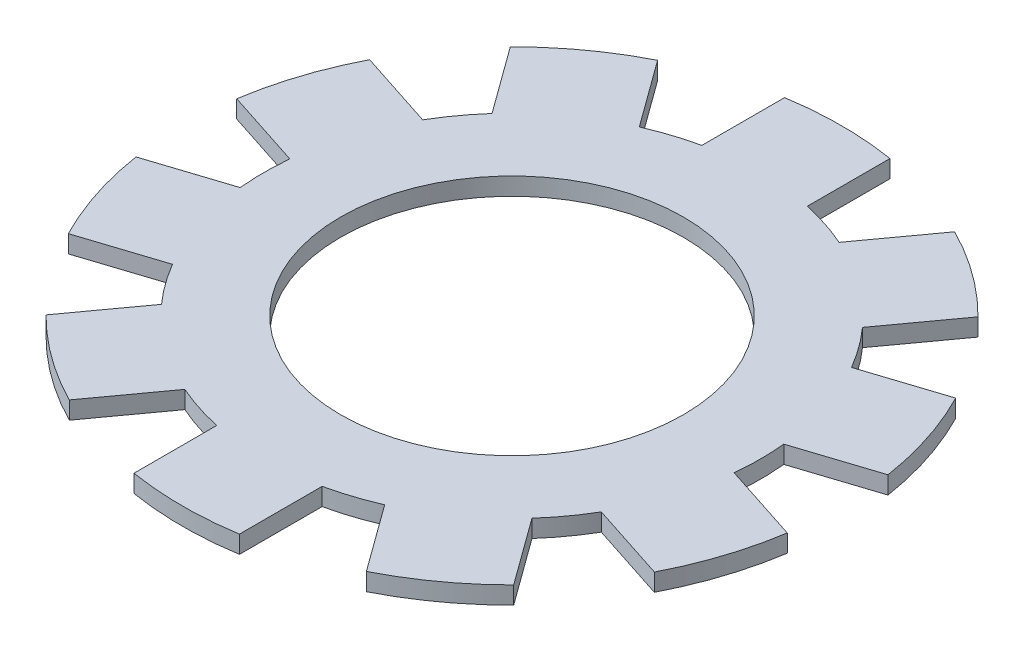
SolidWorks part; units mm, degrees
material "6061 Alloy"
ref_plane "Front Plane" through (0, 0, 0) normal (0, 0, 1) x (1, 0, 0)
ref_plane "Top Plane" through (0, 0, 0) normal (0, 1, 0) x (1, 0, 0)
ref_plane "Right Plane" through (0, 0, 0) normal (1, 0, 0) x (0, 0, -1)
sketch "Sketch1" plane through (0, 0, 0) normal (0, 1, 0) x (1, 0, 0)
  line L0 (-1.2, 5.5211) -> (-1.2, 7.4034)
  line L1 (1.2, 7.4034) -> (1.2, 5.5211)
  line L2 (0, 0) -> (0, 50000) construction
  line L3 (2.2744, 5.172) -> (3.3808, 6.6948)
  line L4 (5.3224, 5.2841) -> (4.216, 3.7613)
  line L5 (4.8801, 2.8474) -> (6.6702, 3.429)
  line L6 (7.4119, 1.1465) -> (5.6217, 0.5648)
  line L7 (5.6217, -0.5648) -> (7.4119, -1.1465)
  line L8 (6.6702, -3.429) -> (4.8801, -2.8474)
  line L9 (4.216, -3.7613) -> (5.3224, -5.2841)
  line L10 (3.3808, -6.6948) -> (2.2744, -5.172)
  line L11 (1.2, -5.5211) -> (1.2, -7.4034)
  line L12 (-1.2, -7.4034) -> (-1.2, -5.5211)
  line L13 (-2.2744, -5.172) -> (-3.3808, -6.6948)
  line L14 (-5.3224, -5.2841) -> (-4.216, -3.7613)
  line L15 (-4.8801, -2.8474) -> (-6.6702, -3.429)
  line L16 (-7.4119, -1.1465) -> (-5.6217, -0.5648)
  line L17 (-5.6217, 0.5648) -> (-7.4119, 1.1465)
  line L18 (-6.6702, 3.429) -> (-4.8801, 2.8474)
  line L19 (-4.216, 3.7613) -> (-5.3224, 5.2841)
  line L20 (-3.3808, 6.6948) -> (-2.2744, 5.172)
  circle A0 centre (0, 0) radius 7.5 construction
  circle A1 centre (0, 0) radius 3.9
  circle A2 centre (0, 0) radius 5.65 construction
  arc A3 (0, 7.5) -> (-1.2, 7.4034) centre (0, 0) ccw
  arc A4 (0, 7.5) -> (1.2, 7.4034) centre (0, 0) cw
  arc A5 (4.4084, 6.0676) -> (5.3224, 5.2841) centre (0, 0) cw
  arc A6 (4.4084, 6.0676) -> (3.3808, 6.6948) centre (0, 0) ccw
  arc A7 (7.1329, 2.3176) -> (7.4119, 1.1465) centre (0, 0) cw
  arc A8 (7.1329, 2.3176) -> (6.6702, 3.429) centre (0, 0) ccw
  arc A9 (7.1329, -2.3176) -> (6.6702, -3.429) centre (0, 0) cw
  arc A10 (7.1329, -2.3176) -> (7.4119, -1.1465) centre (0, 0) ccw
  arc A11 (4.4084, -6.0676) -> (3.3808, -6.6948) centre (0, 0) cw
  arc A12 (4.4084, -6.0676) -> (5.3224, -5.2841) centre (0, 0) ccw
  arc A13 (0, -7.5) -> (-1.2, -7.4034) centre (0, 0) cw
  arc A14 (0, -7.5) -> (1.2, -7.4034) centre (0, 0) ccw
  arc A15 (-4.4084, -6.0676) -> (-5.3224, -5.2841) centre (0, 0) cw
  arc A16 (-4.4084, -6.0676) -> (-3.3808, -6.6948) centre (0, 0) ccw
  arc A17 (-7.1329, -2.3176) -> (-7.4119, -1.1465) centre (0, 0) cw
  arc A18 (-7.1329, -2.3176) -> (-6.6702, -3.429) centre (0, 0) ccw
  arc A19 (-7.1329, 2.3176) -> (-6.6702, 3.429) centre (0, 0) cw
  arc A20 (-7.1329, 2.3176) -> (-7.4119, 1.1465) centre (0, 0) ccw
  arc A21 (-4.4084, 6.0676) -> (-3.3808, 6.6948) centre (0, 0) cw
  arc A22 (-4.4084, 6.0676) -> (-5.3224, 5.2841) centre (0, 0) ccw
  arc A23 (-1.2, 5.5211) -> (-2.2744, 5.172) centre (0, 0) ccw
  arc A24 (2.2744, 5.172) -> (1.2, 5.5211) centre (0, 0) ccw
  arc A25 (4.8801, 2.8474) -> (4.216, 3.7613) centre (0, 0) ccw
  arc A26 (5.6217, -0.5648) -> (5.6217, 0.5648) centre (0, 0) ccw
  arc A27 (4.216, -3.7613) -> (4.8801, -2.8474) centre (0, 0) ccw
  arc A28 (1.2, -5.5211) -> (2.2744, -5.172) centre (0, 0) ccw
  arc A29 (-2.2744, -5.172) -> (-1.2, -5.5211) centre (0, 0) ccw
  arc A30 (-4.8801, -2.8474) -> (-4.216, -3.7613) centre (0, 0) ccw
  arc A31 (-5.6217, 0.5648) -> (-5.6217, -0.5648) centre (0, 0) ccw
  arc A32 (-4.216, 3.7613) -> (-4.8801, 2.8474) centre (0, 0) ccw
  point P8 (1.2, 6.4622)
  point P60 (0, 0)
  point P79 (0, 0)
  dimension "D1" = 15
  dimension "D2" = 7.8
  dimension "D3" = 11.3
  dimension "D4" = 2.4
  dimension "D5" = 10
  dimension "D6" = 10
extrude "Boss-Extrude1" add sketch "Sketch1" along normal blind 0.4
